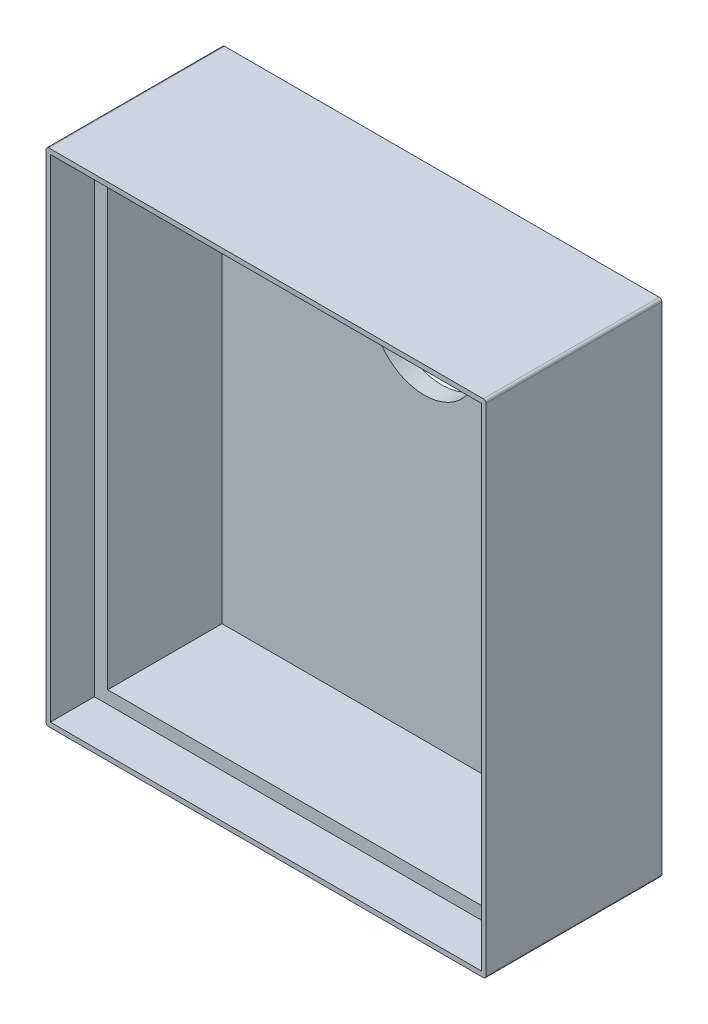
SolidWorks part; units mm, degrees
ref_plane "Front" through (0, 0, 0) normal (0, 0, 1) x (1, 0, 0)
ref_plane "Top" through (0, 0, 0) normal (0, 1, 0) x (1, 0, 0)
ref_plane "Right" through (0, 0, 0) normal (1, 0, 0) x (0, 0, -1)
sketch "草图1" plane through (0, 0, 0) normal (0, 0, 1) x (1, 0, 0)
  line L1 (3, 0) -> (497, 0)
  line L2 (0, -3) -> (0, -567)
  line L3 (3, -570) -> (497, -570)
  line L4 (500, -3) -> (500, -567)
  arc A0 (497, -570) -> (500, -567) centre (497, -567) ccw
  arc A1 (3, -570) -> (0, -567) centre (3, -567) cw
  arc A2 (497, 0) -> (500, -3) centre (497, -3) cw
  arc A3 (0, -3) -> (3, 0) centre (3, -3) cw
  point P7 (500, -570)
  point P12 (500, 0)
  point P15 (0, 0)
  dimension "D3" = 3
  dimension "D1" = 500
  dimension "D2" = 570
extrude "凸台-拉伸1" add sketch "草图1" along normal blind 200
shell "抽壳1" thickness 20
sketch "草图2" plane through (0, 0, 200) normal (0, 0, 1) x (1, 0, 0)
  line L0 (250, -285) -> (99.7674, -285) construction
  line L1 (480, -20) -> (20, -20) construction
  line L2 (250, -20) -> (250, -550) construction
  line L3 (20, -550) -> (480, -550) construction
  line L4 (250, -285) -> (250, -5.49)
  line L5 (4.785, -5.49) -> (495.215, -5.49)
  line L6 (495.215, -5.49) -> (495.215, -20)
  line L7 (4.785, -564.51) -> (495.215, -564.51)
  line L8 (495.215, -564.51) -> (495.215, -550)
  line L9 (495.215, -20) -> (495.215, -550)
  line L10 (4.785, -564.51) -> (4.785, -550)
  line L11 (4.785, -5.49) -> (4.785, -20)
  line L12 (4.785, -20) -> (4.785, -550)
  point P15 (250, -564.51)
extrude "切除-拉伸1" cut sketch "草图2" against normal blind 50
sketch "草图3" plane through (0, 0, 0) normal (0, 0, -1) x (-1, 0, 0)
  line L0 (-250, 0) -> (-250, -150) construction
  line L1 (-497, 0) -> (-3, 0) construction
  circle A0 centre (-250, -150) radius 60
extrude "切除-拉伸2" cut sketch "草图3" against normal blind 50
